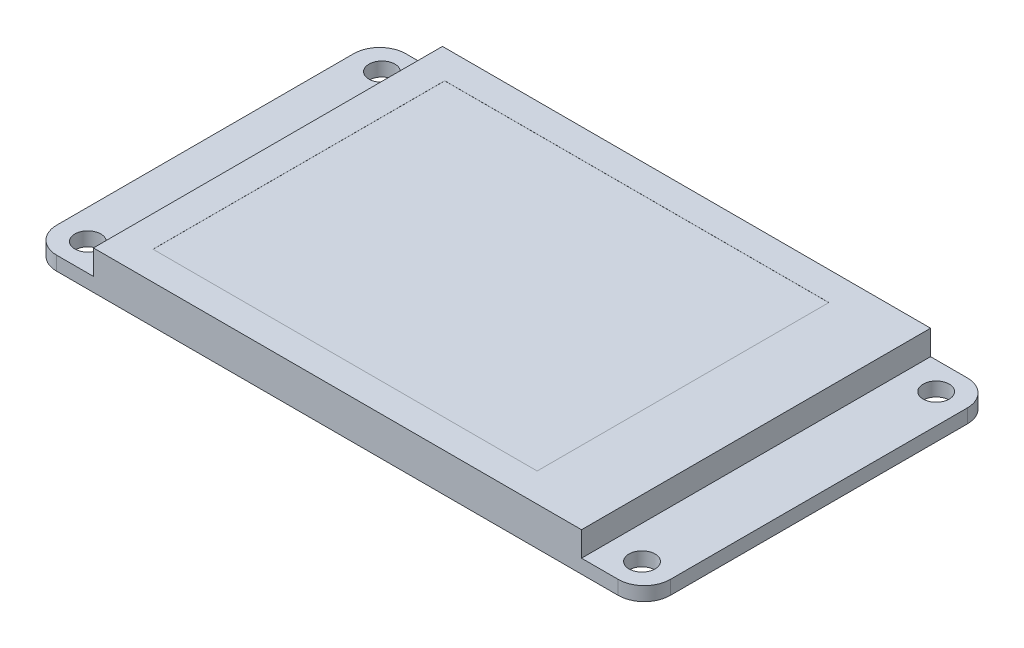
SolidWorks part; units mm, degrees
ref_plane "前基準面" through (0, 0, 0) normal (0, 0, 1) x (1, 0, 0)
ref_plane "上基準面" through (0, 0, 0) normal (0, 1, 0) x (1, 0, 0)
ref_plane "右基準面" through (0, 0, 0) normal (1, 0, 0) x (0, 0, -1)
sketch "草圖1" plane through (0, 0, 0) normal (0, 1, 0) x (1, 0, 0)
  line L1 (-37.982, 23.2596) -> (32.668, 23.2596)
  line L2 (-37.982, 23.2596) -> (-37.982, -16.9304)
  line L3 (-37.982, -16.9304) -> (32.668, -16.9304)
  line L4 (32.668, 23.2596) -> (32.668, -16.9304)
  dimension "D1" = 70.65
  dimension "D2" = 40.19
extrude "填料-伸長1" add sketch "草圖1" along normal blind 1.6
fillet "圓角1" radius 3 4 edges at (32.668, 0.8, 16.9304) (32.668, 0.8, -23.2596) (-37.982, 0.8, -23.2596) (-37.982, 0.8, 16.9304)
sketch "草圖2" plane through (0, 1.6, 0) normal (0, 1, 0) x (1, 0, 0)
  line L0 (29.668, 23.2596) -> (-34.982, 23.2596) construction
  line L1 (-37.982, 20.2596) -> (-37.982, -13.9304) construction
  line L3 (-34.982, -16.9304) -> (29.668, -16.9304) construction
  line L4 (32.668, -13.9304) -> (32.668, 20.2596) construction
  circle A0 centre (-34.562, 20.0996) radius 1.5
  circle A1 centre (29.248, 20.0996) radius 1.5
  circle A2 centre (-34.562, -13.7704) radius 1.5
  circle A3 centre (29.248, -13.7704) radius 1.5
  point P8 (0, 0)
  point P13 (0, 0)
  point P15 (-34.1265, -16.9304)
  point P21 (21.0994, 23.2596)
  dimension "D1" = 3
  dimension "D2" = 3
  dimension "D3" = 3
  dimension "D4" = 3
  dimension "D9" = 3.42
  dimension "D5" = 3.16
  dimension "D6" = 3.42
  dimension "D7" = 3.42
  dimension "D8" = 3.16
  dimension "D10" = 3.42
  dimension "D11" = 3.16
  dimension "D12" = 3.16
  dimension "D13" = 33.87
  dimension "D14" = 63.81
extrude "除料-伸長1" cut sketch "草圖2" against normal blind 1.6
sketch "草圖3" plane through (0, 1.6, 0) normal (0, 1, 0) x (1, 0, 0)
  line L0 (29.668, 23.2596) -> (-34.982, 23.2596) construction
  line L1 (-30.757, 23.2596) -> (25.443, 23.2596)
  line L2 (-30.757, 23.2596) -> (-30.757, -16.9304)
  line L3 (-30.757, -16.9304) -> (25.443, -16.9304)
  line L4 (25.443, 23.2596) -> (25.443, -16.9304)
  line L5 (-34.982, -16.9304) -> (29.668, -16.9304) construction
  line L6 (-37.982, 20.2596) -> (-37.982, -13.9304) construction
  line L7 (32.668, -13.9304) -> (32.668, 20.2596) construction
  dimension "D1" = 56.2
  dimension "D2" = 0
  dimension "D3" = 0
  dimension "D4" = 7.225
  dimension "D5" = 7.225
extrude "填料-伸長2" add sketch "草圖3" along normal blind 2.84
sketch "草圖4" plane through (0, 4.44, 0) normal (0, 1, 0) x (1, 0, 0)
  line L0 (-30.757, 23.2596) -> (-30.757, -16.9304) construction
  line L1 (-27.197, 19.9596) -> (17.033, 19.9596)
  line L2 (-27.197, 19.9596) -> (-27.197, -13.6304)
  line L3 (-27.197, -13.6304) -> (17.033, -13.6304)
  line L4 (17.033, 19.9596) -> (17.033, -13.6304)
  line L5 (25.443, -16.9304) -> (25.443, 23.2596) construction
  line L6 (25.443, 23.2596) -> (-30.757, 23.2596) construction
  line L7 (-30.757, -16.9304) -> (25.443, -16.9304) construction
  circle A0 centre (-34.562, 20.0996) radius 1.5 construction
  circle A1 centre (29.248, 20.0996) radius 1.5 construction
  circle A2 centre (-34.562, -13.7704) radius 1.5 construction
  circle A3 centre (29.248, -13.7704) radius 1.5 construction
  dimension "D7" = 7.365
  dimension "D9" = 7.365
  dimension "D12" = 12.215
  dimension "D1" = 3.56
  dimension "D2" = 8.41
  dimension "D3" = 3.3
  dimension "D4" = 3.3
  dimension "D5" = 44.23
  dimension "D6" = 33.59
  dimension "D8" = 12.215
  dimension "D10" = 12.215
  dimension "D11" = 0.14
extrude "除料-伸長2" cut sketch "草圖4" against normal blind 0.01
